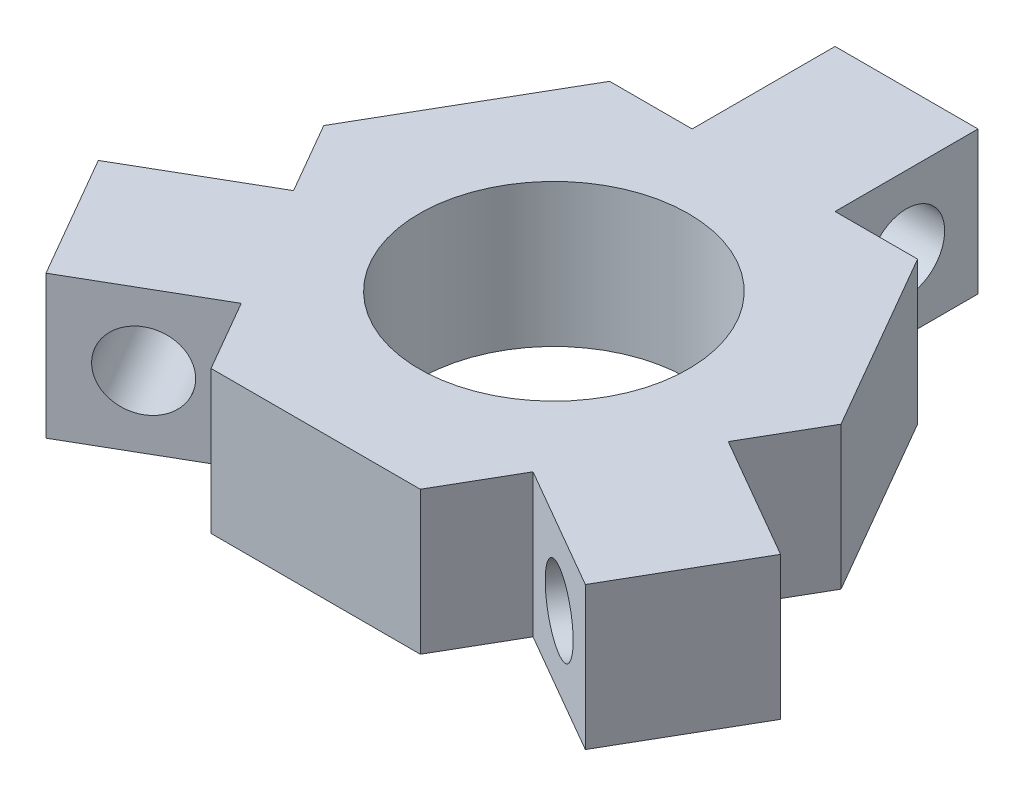
SolidWorks part; units mm, degrees
ref_plane "前视基准面" through (0, 0, 0) normal (0, 0, 1) x (1, 0, 0)
ref_plane "上视基准面" through (0, 0, 0) normal (0, 1, 0) x (1, 0, 0)
ref_plane "右视基准面" through (0, 0, 0) normal (1, 0, 0) x (0, 0, -1)
sketch "草图1" plane through (0, 0, 0) normal (0, 1, 0) x (1, 0, 0)
  line L0 (-6.4641, 8.8038) -> (6.4641, 8.8038)
  line L1 (0, 20) -> (-17.3205, -10)
  line L2 (-17.3205, -10) -> (17.3205, -10)
  line L3 (17.3205, -10) -> (0, 20)
  line L4 (4.3923, -10) -> (10.8564, 1.1962)
  line L5 (-10.8564, 1.1962) -> (-4.3923, -10)
  line L6 (-3, 8.8038) -> (-3, 14.8038)
  line L7 (-3, 14.8038) -> (3, 14.8038)
  line L8 (3, 14.8038) -> (3, 8.8038)
  line L9 (6.1244, -7) -> (11.3205, -10)
  line L10 (11.3205, -10) -> (14.3205, -4.8038)
  line L11 (14.3205, -4.8038) -> (9.1244, -1.8038)
  line L12 (-9.1244, -1.8038) -> (-14.3205, -4.8038)
  line L14 (-14.3205, -4.8038) -> (-11.3205, -10)
  line L15 (0, 14.8038) -> (0, 8.8038) construction
  line L16 (7.6244, -4.4019) -> (12.8205, -7.4019) construction
  line L17 (-11.3205, -10) -> (-6.1244, -7)
  line L18 (-12.8205, -7.4019) -> (-7.6244, -4.4019) construction
  circle A0 centre (0, 0) radius 10 construction
  point P21 (13.9377, -10)
  point P23 (14.6231, -5.3279)
  point P32 (10.9389, -3.6807)
  point P33 (4.5989, -5.3383)
  dimension "D1" = 20
  dimension "D2" = 6
extrude "凸台-拉伸2" add sketch "草图1" along normal blind 6 contours L1 L5 L2 L4 L3 L0 | L14 L17 L5 L12 | L10 L11 L4 L9 | L8 L7 L6 L0
sketch "草图6" plane through (-1.5, 0, -2.5981) normal (-0.5, 0, -0.866) x (-0.866, 0, 0.5)
  line L1 (14.8038, 0) -> (8.8038, 0)
  line L2 (14.8038, 0) -> (14.8038, 6)
  line L3 (14.8038, 6) -> (8.8038, 6)
  line L4 (8.8038, 0) -> (8.8038, 6)
  line L5 (11.8038, 6) -> (11.8038, 0) construction
  line L6 (14.8038, 3) -> (8.8038, 3) construction
  circle A0 centre (11.8038, 3) radius 1.6
  point P96 (11.8038, 3)
extrude "切除-拉伸5" cut sketch "草图6" against normal blind 6 contours A0
sketch "草图7" plane through (3, 0, 0) normal (1, 0, 0) x (0, 0, -1)
  line L1 (14.8038, 0) -> (8.8038, 0)
  line L2 (14.8038, 0) -> (14.8038, 6)
  line L3 (14.8038, 6) -> (8.8038, 6)
  line L4 (8.8038, 0) -> (8.8038, 6)
  line L5 (11.8038, 6) -> (11.8038, 0) construction
  line L6 (14.8038, 3) -> (8.8038, 3) construction
  circle A0 centre (11.8038, 3) radius 1.6
  point P160 (11.8038, 3)
extrude "切除-拉伸6" cut sketch "草图7" against normal blind 6 contours A0
sketch "草图8" plane through (-1.5, 0, 2.5981) normal (-0.5, 0, 0.866) x (0.866, 0, 0.5)
  line L1 (14.8038, 0) -> (8.8038, 0)
  line L2 (14.8038, 0) -> (14.8038, 6)
  line L3 (14.8038, 6) -> (8.8038, 6)
  line L4 (8.8038, 0) -> (8.8038, 6)
  line L5 (11.8038, 6) -> (11.8038, 0) construction
  line L6 (14.8038, 3) -> (8.8038, 3) construction
  circle A0 centre (11.8038, 3) radius 1.6
  point P236 (11.8038, 3)
extrude "切除-拉伸7" cut sketch "草图8" against normal blind 6 contours A0
sketch "草图9" plane through (0, 0, 0) normal (0, -1, 0) x (1, 0, 0)
  circle A0 centre (0, 0) radius 5.65
  dimension "D1" = 11.3
extrude "切除-拉伸9" cut sketch "草图9" against normal blind 6
